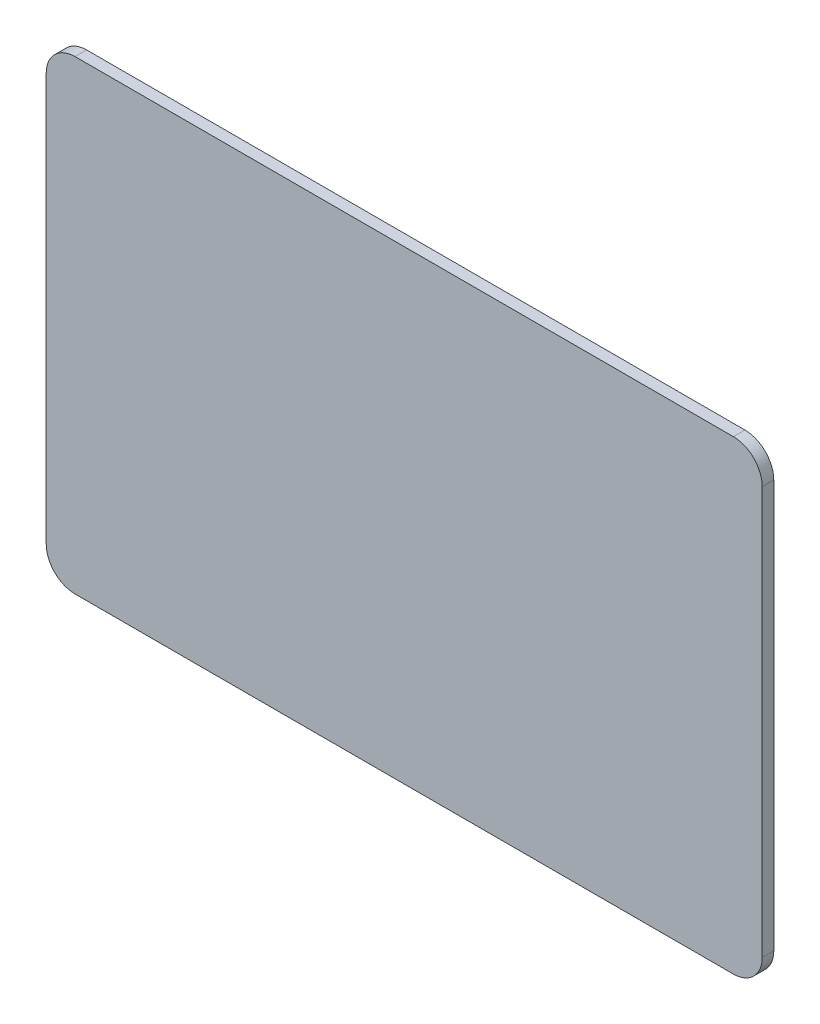
SolidWorks part; units mm, degrees
ref_plane "Plano frontal" through (0, 0, 0) normal (0, 0, 1) x (1, 0, 0)
ref_plane "Plano superior" through (0, 0, 0) normal (0, 1, 0) x (1, 0, 0)
ref_plane "Plano direito" through (0, 0, 0) normal (1, 0, 0) x (0, 0, -1)
sketch "Esboço1" plane through (0, 0, 0) normal (0, 0, 1) x (1, 0, 0)
  line L0 (32.1484, -17.5286) -> (32.1484, 17.7714)
  line L1 (29.6484, 20.2714) -> (-27.3516, 20.2714)
  line L2 (-29.8516, 17.7714) -> (-29.8516, -17.5286)
  line L3 (-27.3516, -20.0286) -> (29.6484, -20.0286)
  arc A0 (32.1484, 17.7714) -> (29.6484, 20.2714) centre (29.6484, 17.7714) ccw
  arc A1 (-27.3516, 20.2714) -> (-29.8516, 17.7714) centre (-27.3516, 17.7714) ccw
  arc A2 (-29.8516, -17.5286) -> (-27.3516, -20.0286) centre (-27.3516, -17.5286) ccw
  arc A3 (29.6484, -20.0286) -> (32.1484, -17.5286) centre (29.6484, -17.5286) ccw
extrude "Ressalto-extrusão1" add sketch "Esboço1" along normal blind 1
